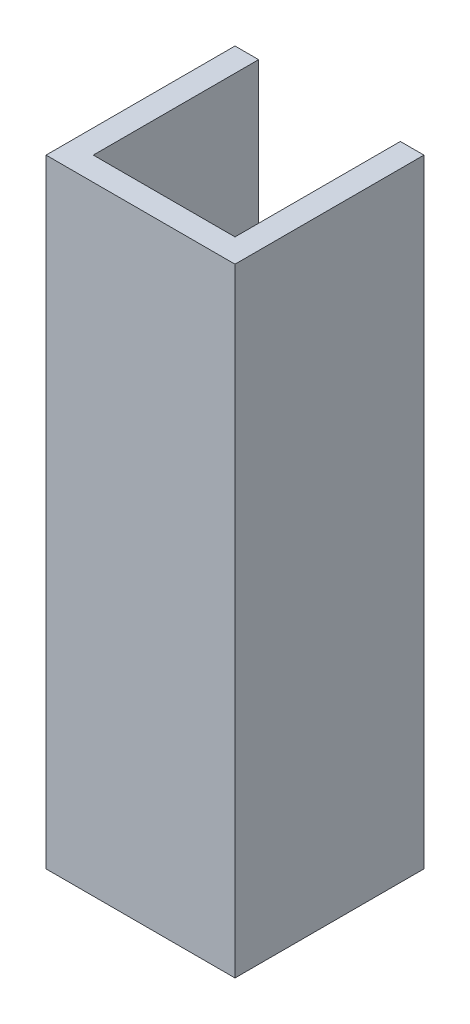
SolidWorks part; units mm, degrees
material "1060 Alloy"
ref_plane "Front Plane" through (0, 0, 0) normal (0, 0, 1) x (1, 0, 0)
ref_plane "Top Plane" through (0, 0, 0) normal (0, 1, 0) x (1, 0, 0)
ref_plane "Right Plane" through (0, 0, 0) normal (1, 0, 0) x (0, 0, -1)
sketch "Sketch1" plane through (0, 0, 0) normal (0, 1, 0) x (1, 0, 0)
  line L0 (0, 0) -> (25.4, 0)
  line L1 (25.4, 0) -> (25.4, 25.4)
  line L7 (0, 25.4) -> (0, 0)
  dimension "D1" = 25.4
  dimension "D2" = 25.4
  dimension "D3" = 25.4
extrude "Extrude-Thin1" add sketch "Sketch1" along normal blind 83.1 thin thin type one direction reverse wall 3.175
